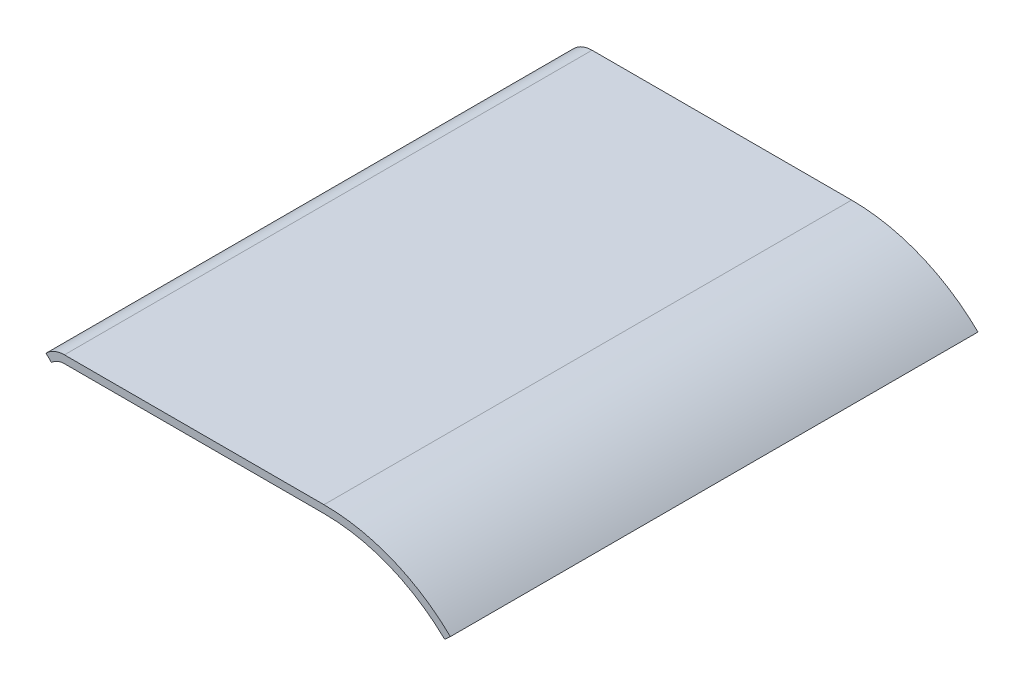
SolidWorks part; units mm, degrees
ref_plane "Front Plane" through (0, 0, 0) normal (0, 0, 1) x (1, 0, 0)
ref_plane "Top Plane" through (0, 0, 0) normal (0, 1, 0) x (1, 0, 0)
ref_plane "Right Plane" through (0, 0, 0) normal (1, 0, 0) x (0, 0, -1)
sketch "Sketch1" plane through (0, 0, 0) normal (0, 0, 1) x (1, 0, 0)
  line L0 (0, 0) -> (101.34, 0)
  line L1 (-7.1934, -3.0534) -> (-14.8473, -10.9792) construction
  line L2 (150.6885, -19.9381) -> (178.3104, -46.6123) construction
  line L3 (150.6885, -19.9381) -> (112.4704, -54.3498) construction
  line L4 (150.6885, -19.9381) -> (148.4534, -21.9506)
  line L5 (-5.0354, -5.1374) -> (-12.227, -12.5846) construction
  line L6 (0, -3) -> (101.34, -3)
  line L7 (-7.1934, -3.0534) -> (-5.0354, -5.1374)
  arc A0 (101.34, 0) -> (150.6885, -19.9381) centre (101.34, -71.04) cw
  arc A1 (0, 0) -> (-7.1934, -3.0534) centre (0, -10) ccw
  arc A2 (101.34, -3) -> (148.4534, -21.9506) centre (101.34, -71.04) cw
  arc A3 (0, -3) -> (-5.0354, -5.1374) centre (0, -10) ccw
  dimension "D1" = 10
  dimension "D4" = 71.04
  dimension "D2" = 134
  dimension "D3" = 101.34
  dimension "D5" = 94
  dimension "D6" = 3
extrude "Boss-Extrude1" add sketch "Sketch1" along normal blind 206
